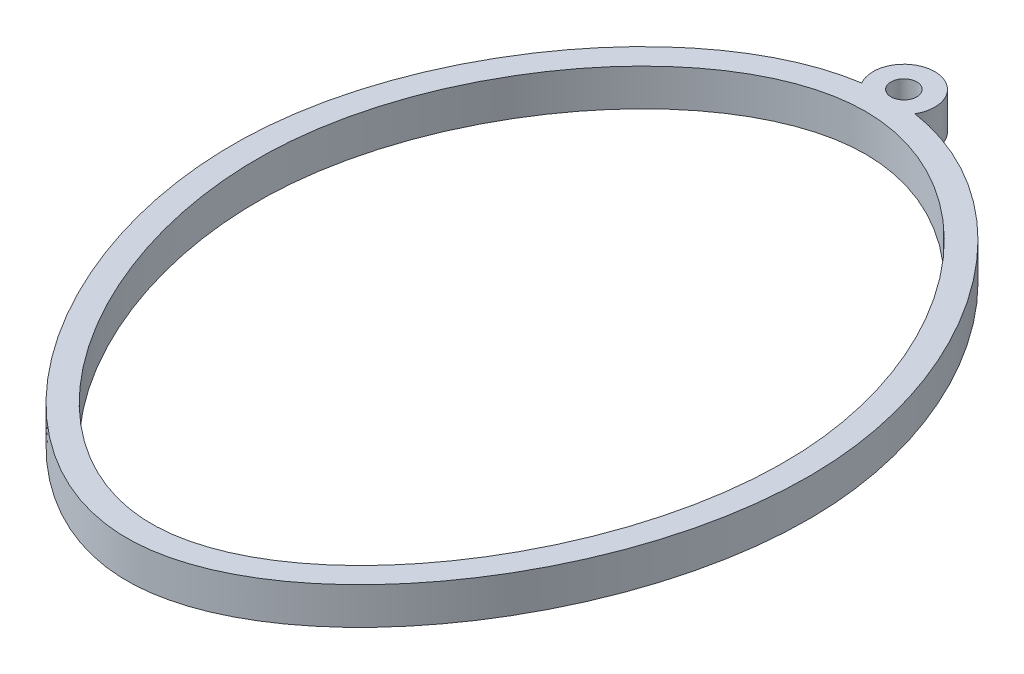
SolidWorks part; units mm, degrees
ref_plane "Front Plane" through (0, 0, 0) normal (0, 0, 1) x (1, 0, 0)
ref_plane "Top Plane" through (0, 0, 0) normal (0, 1, 0) x (1, 0, 0)
ref_plane "Right Plane" through (0, 0, 0) normal (1, 0, 0) x (0, 0, -1)
sketch "Sketch1" plane through (0, 0, 0) normal (0, 1, 0) x (1, 0, 0)
  line L0 (0, 26.0581) -> (0, -31.8488) construction
  line L1 (-21.27, 0) -> (21.27, 0) construction
  line L2 (0, 28.0581) -> (0, -33.8488) construction
  line L3 (-23.27, 0) -> (23.27, 0) construction
  circle A0 centre (0, 29.1581) radius 1.05
  arc A1 (2.1565, 27.8934) -> (-2.1565, 27.8934) centre (0, 29.1581) ccw
  spline S0 degree 3 poles (-32.0246, -0.8485) (0, 38.6397) (32.0246, -0.8485) (0, -48.3535) (-32.0246, -0.8485) (0, 38.6397) (32.0246, -0.8485) knots -0.7662 -0.5 -0.2338 0 0.2338 0.5 0.7662 1 1.2338 1.5 1.7662 only from (0, 26.0581) to (0, 26.0581)
  spline S1 degree 3 poles (-35.0158, -0.7894) (0, 41.6217) (35.0158, -0.7894) (0, -51.3644) (-35.0158, -0.7894) (0, 41.6217) (35.0158, -0.7894) knots -0.764911 -0.5 -0.235089 0 0.235089 0.5 0.764911 1 1.235089 1.5 1.764911 only from (0, 28.0581) to (0, 28.0581)
  dimension "D9" = 2.1
  dimension "D10" = 5
  dimension "D1" = 57.907
  dimension "D2" = 42.54
  dimension "D3" = 26.0581
  dimension "D4" = 21.27
  dimension "D5" = 61.907
  dimension "D6" = 2
  dimension "D7" = 46.54
  dimension "D8" = 2
  dimension "D11" = 3.1
extrude "Boss-Extrude1" add sketch "Sketch1" along normal blind 3 contours A1 S1 A0 | S1 S0
equation "\"D7@Sketch1\"=\"D2@Sketch1\"+4"
equation "\"D5@Sketch1\"=\"D1@Sketch1\"+4"
equation "\"D3@Sketch1\"=\"D1@Sketch1\"*0.45"
equation "\"D4@Sketch1\"=\"D2@Sketch1\"*0.5"
